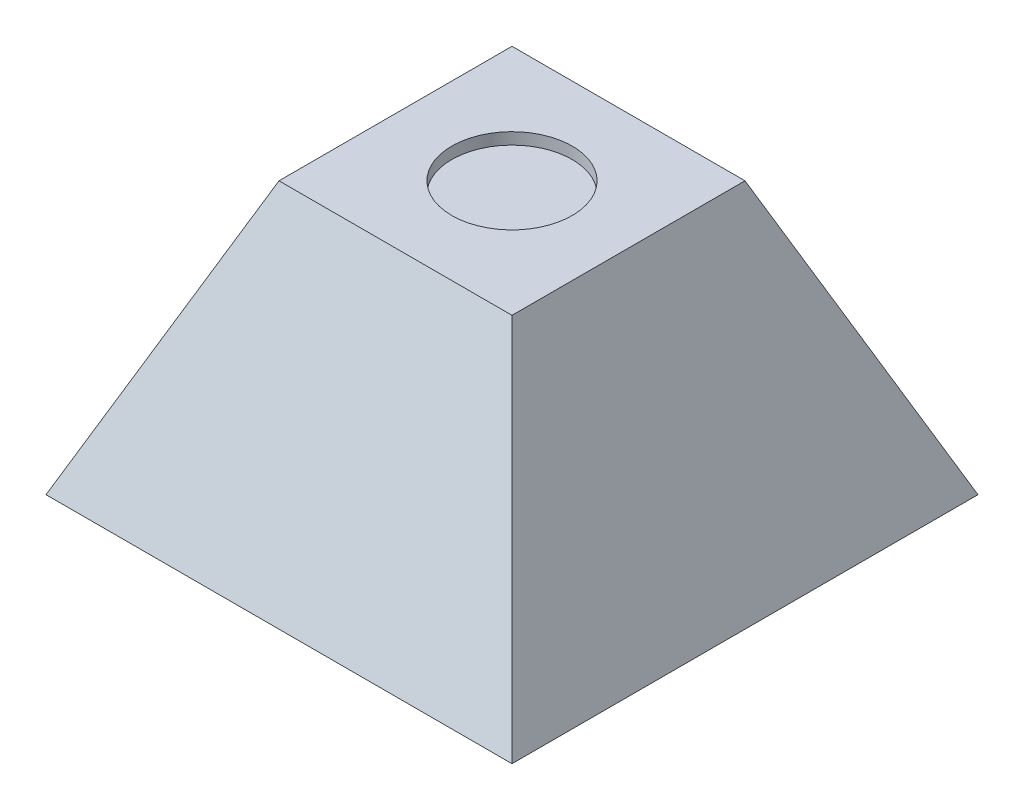
SolidWorks part; units mm, degrees
ref_plane "前视基准面" through (0, 0, 0) normal (0, 0, 1) x (1, 0, 0)
ref_plane "上视基准面" through (0, 0, 0) normal (0, 1, 0) x (1, 0, 0)
ref_plane "右视基准面" through (0, 0, 0) normal (1, 0, 0) x (0, 0, -1)
other "Configuration Table"
sketch "草图1" plane through (0, 0, 0) normal (0, 1, 0) x (1, 0, 0)
  line L1 (-60, -60) -> (60, -60)
  line L2 (-60, -60) -> (-60, 60)
  line L3 (-60, 60) -> (60, 60)
  line L4 (60, -60) -> (60, 60)
  line L5 (-60, -60) -> (60, 60) construction
  line L6 (-60, 60) -> (60, -60) construction
  point P0 (0, 0)
  dimension "D1" = 120
ref_plane "基准面1" through (0, 70, 0) normal (0, 1, 0) x (1, 0, 0)
sketch "草图2" plane through (0, 70, 0) normal (0, 1, 0) x (1, 0, 0)
  line L0 (-60, -60) -> (60, 60) construction
  line L1 (-30, -30) -> (30, -30)
  line L2 (-30, -30) -> (-30, 30)
  line L3 (-30, 30) -> (30, 30)
  line L4 (30, -30) -> (30, 30)
  line L5 (-30, -30) -> (30, 30) construction
  line L6 (-30, 30) -> (30, -30) construction
  point P0 (0, 0)
  dimension "D1" = 60
loft "放样1" add profiles "草图2", "草图1"
sketch "草图3" plane through (0, 70, 0) normal (0, 1, 0) x (1, 0, 0)
  circle A0 centre (0, 0) radius 15.5
  dimension "D1" = 31
extrude "切除-拉伸1" cut sketch "草图3" against normal blind 3
